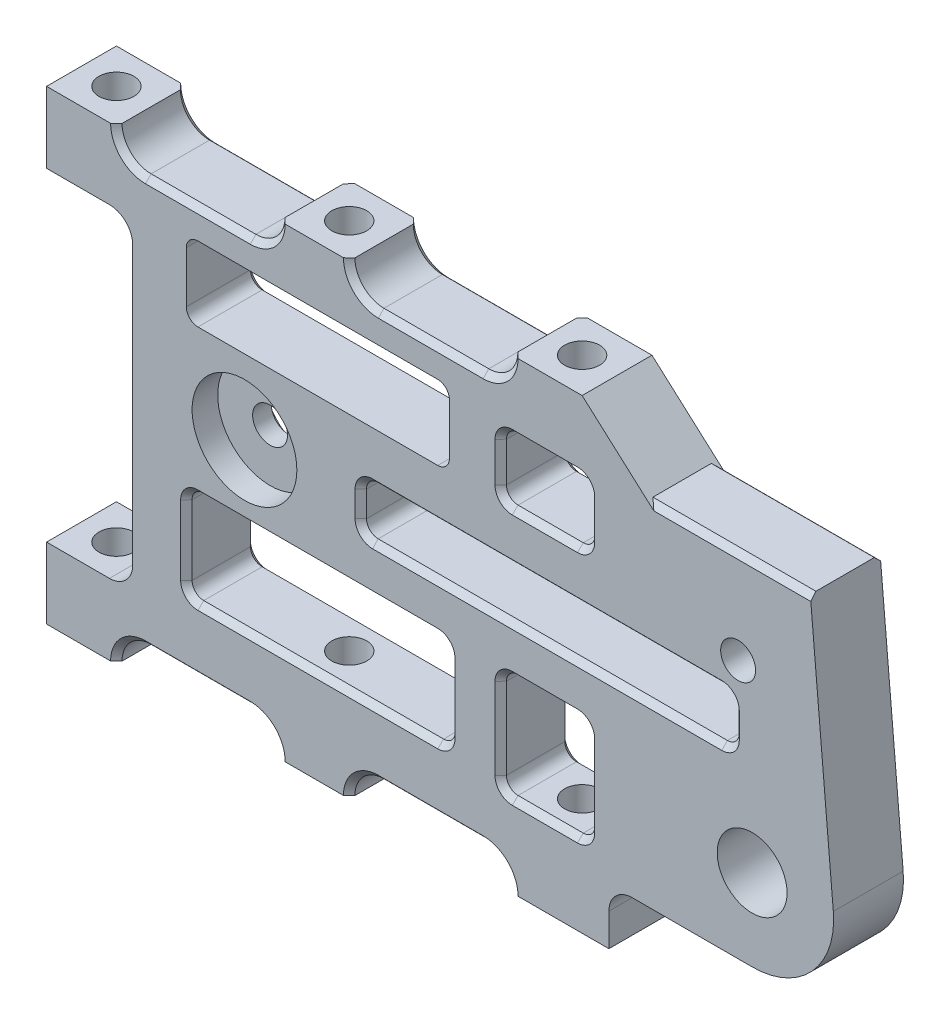
SolidWorks part; units mm, degrees
material "6061 合金"
ref_plane "前视基准面" through (0, 0, 0) normal (0, 0, 1) x (1, 0, 0)
ref_plane "上视基准面" through (0, 0, 0) normal (0, 1, 0) x (1, 0, 0)
ref_plane "右视基准面" through (0, 0, 0) normal (1, 0, 0) x (0, 0, -1)
ref_plane "基准面1" through (0, 0, 0) normal (0, 0, -1) x (-1, 0, 0)
sketch "草图1" plane through (0, 0, 0) normal (0, 0, -1) x (-1, 0, 0)
  line L0 (-32.3626, 20) -> (-35.8621, -20)
  line L1 (-35.8621, -20) -> (32.8, -20)
  line L2 (32.8, -20) -> (32.8, 20)
  line L3 (32.8, 20) -> (-32.3626, 20)
extrude "凸台-拉伸1" add sketch "草图1" against normal blind 6
sketch "草图2" plane through (0, 0, 6) normal (0, 0, 1) x (1, 0, 0)
  line L0 (35.4422, -15.2) -> (15.5, -15.2)
  line L1 (15.5, -15.2) -> (15.5, -20)
  line L2 (15.5, -20) -> (35.8621, -20)
  line L3 (35.8621, -20) -> (35.4422, -15.2)
extrude "切除-拉伸1" cut sketch "草图2" against normal through all
sketch "草图3" plane through (0, 0, 6) normal (0, 0, 1) x (1, 0, 0)
  line L0 (-6.8, -20) -> (7.2, -20)
  line L1 (4.7, -17.5) -> (-4.3, -17.5)
  arc A0 (7.2, -20) -> (4.7, -17.5) centre (4.7, -20) ccw
  arc A1 (-4.3, -17.5) -> (-6.8, -20) centre (-4.3, -20) ccw
extrude "切除-拉伸2" cut sketch "草图3" against normal through all
sketch "草图4" plane through (0, 0, 6) normal (0, 0, 1) x (1, 0, 0)
  line L0 (-26.8, -20) -> (-12.8, -20)
  line L1 (-15.3, -17.5) -> (-24.3, -17.5)
  arc A0 (-12.8, -20) -> (-15.3, -17.5) centre (-15.3, -20) ccw
  arc A1 (-24.3, -17.5) -> (-26.8, -20) centre (-24.3, -20) ccw
extrude "切除-拉伸3" cut sketch "草图4" against normal through all
sketch "草图5" plane through (0, 0, 6) normal (0, 0, 1) x (1, 0, 0)
  line L0 (-32.8, 13.9) -> (-32.8, -13.9)
  line L1 (-32.8, -13.9) -> (-25.4, -13.9)
  line L2 (-25.4, -13.9) -> (-25.4, 13.9)
  line L3 (-25.4, 13.9) -> (-32.8, 13.9)
extrude "切除-拉伸4" cut sketch "草图5" against normal through all
sketch "草图6" plane through (0, 0, 6) normal (0, 0, 1) x (1, 0, 0)
  line L0 (-12.8, 20) -> (-26.8, 20)
  line L1 (-24.3, 17.5) -> (-15.3, 17.5)
  arc A0 (-26.8, 20) -> (-24.3, 17.5) centre (-24.3, 20) ccw
  arc A1 (-15.3, 17.5) -> (-12.8, 20) centre (-15.3, 20) ccw
extrude "切除-拉伸5" cut sketch "草图6" against normal through all
sketch "草图7" plane through (0, 0, 6) normal (0, 0, 1) x (1, 0, 0)
  line L0 (7.2, 20) -> (-6.8, 20)
  line L1 (-4.3, 17.5) -> (4.7, 17.5)
  arc A0 (-6.8, 20) -> (-4.3, 17.5) centre (-4.3, 20) ccw
  arc A1 (4.7, 17.5) -> (7.2, 20) centre (4.7, 20) ccw
extrude "切除-拉伸6" cut sketch "草图7" against normal through all
sketch "草图8" plane through (0, 0, 6) normal (0, 0, 1) x (1, 0, 0)
  line L0 (13.2, 20) -> (18.8, 15)
  line L1 (18.8, 15) -> (32.8, 15)
  line L2 (32.8, 15) -> (32.3626, 20)
  line L3 (32.3626, 20) -> (13.2, 20)
extrude "切除-拉伸7" cut sketch "草图8" against normal through all
sketch "草图9" plane through (0, 0, 0) normal (0, 0, -1) x (-1, 0, 0)
  line L0 (-13.8, -13) -> (-6.2, -13)
  line L1 (-6.2, -13) -> (-6.2, -4)
  line L2 (-6.2, -4) -> (-13.8, -4)
  line L3 (-13.8, -4) -> (-13.8, -13)
extrude "切除-拉伸8" cut sketch "草图9" against normal through all
sketch "草图10" plane through (0, 0, 0) normal (0, 0, -1) x (-1, 0, 0)
  line L0 (-1.8, -12) -> (20.8, -12)
  line L1 (20.8, -12) -> (20.8, -4)
  line L2 (20.8, -4) -> (-1.8, -4)
  line L3 (-1.8, -4) -> (-1.8, -12)
extrude "切除-拉伸9" cut sketch "草图10" against normal through all
sketch "草图11" plane through (0, 0, 0) normal (0, 0, -1) x (-1, 0, 0)
  line L0 (-1.8, 15) -> (-1.8, 8.6)
  line L1 (-1.8, 8.6) -> (20.8, 8.6)
  line L2 (20.8, 8.6) -> (20.8, 15)
  line L3 (20.8, 15) -> (-1.8, 15)
extrude "切除-拉伸10" cut sketch "草图11" against normal through all
sketch "草图12" plane through (0, 0, 0) normal (0, 0, -1) x (-1, 0, 0)
  line L0 (-13.8, 8.6) -> (-6.2, 8.6)
  line L1 (-6.2, 8.6) -> (-6.2, 14)
  line L2 (-6.2, 14) -> (-13.8, 14)
  line L3 (-13.8, 14) -> (-13.8, 8.6)
extrude "切除-拉伸11" cut sketch "草图12" against normal through all
sketch "草图13" plane through (0, 0, 6) normal (0, 0, 1) x (1, 0, 0)
  line L0 (-5.8, 0.1) -> (26.2, 0.1)
  line L1 (26.2, 0.1) -> (26.2, 4.3)
  line L2 (26.2, 4.3) -> (-5.8, 4.3)
  line L3 (-5.8, 4.3) -> (-5.8, 0.1)
extrude "切除-拉伸12" cut sketch "草图13" against normal through all
hole_wizard "Ø3.0 (3) 直径孔1" positions "草图15" profile "草图14" hole size "Ø3.0" standard "ANSI Metric"
sketch "草图15" plane through (0, 0, 6) normal (0, 0, 1) x (1, 0, 0)
  point P0 (26.6, 7)
sketch "草图14" plane through (26.6, 7, 6) normal (1, 0, 0) x (0, -1, 0)
  line L0 (0, 0) -> (0, 6)
  line L1 (0, 6) -> (1.5, 6)
  line L2 (1.5, 6) -> (1.5, 0)
  line L5 (1.5, 0) -> (0, 0)
  line L11 (0, -6.35) -> (0, 107.95) construction
  dimension "通孔孔直径" = 3
  dimension "通孔孔深度" = 6
hole_wizard "Ø6.0 (6) 直径孔1" positions "草图17" profile "草图16" hole size "Ø6.0" standard "ANSI Metric"
sketch "草图17" plane through (0, 0, 6) normal (0, 0, 1) x (1, 0, 0)
  point P0 (27.803, -8.2)
sketch "草图16" plane through (27.803, -8.2, 6) normal (1, 0, 0) x (0, -1, 0)
  line L0 (0, 0) -> (0, 6)
  line L1 (0, 6) -> (3, 6)
  line L2 (3, 6) -> (3, 0)
  line L5 (3, 0) -> (0, 0)
  line L11 (0, -6.35) -> (0, 107.95) construction
  dimension "通孔孔直径" = 6
  dimension "通孔孔深度" = 6
hole_wizard "Ø3.0 (3) 直径孔2" positions "草图19" profile "草图18" hole size "Ø3.0" standard "ANSI Metric"
sketch "草图19" plane through (0, -13, 0) normal (0, 1, 0) x (1, 0, 0)
  point P0 (10.2, -3)
cosmetic thread "装饰螺纹线4" parameters "D2"=3.5
sketch "草图18" plane through (10.2, -13, 3) normal (1, 0, 0) x (0, 0, 1)
  line L0 (0, 0) -> (0, 7)
  line L1 (0, 7) -> (1.5, 7)
  line L2 (1.5, 7) -> (1.5, 0)
  line L5 (1.5, 0) -> (0, 0)
  line L11 (0, -6.35) -> (0, 107.95) construction
  dimension "通孔孔直径" = 3
  dimension "通孔孔深度" = 7
hole_wizard "Ø3.0 (3) 直径孔3" positions "草图21" profile "草图20" hole size "Ø3.0" standard "ANSI Metric"
sketch "草图21" plane through (0, -12, 0) normal (0, 1, 0) x (1, 0, 0)
  point P0 (-9.8, -3)
sketch "草图20" plane through (-9.8, -12, 3) normal (1, 0, 0) x (0, 0, 1)
  line L0 (0, 0) -> (0, 8)
  line L1 (0, 8) -> (1.5, 8)
  line L2 (1.5, 8) -> (1.5, 0)
  line L5 (1.5, 0) -> (0, 0)
  line L11 (0, -6.35) -> (0, 107.95) construction
  dimension "通孔孔直径" = 3
  dimension "通孔孔深度" = 8
cosmetic thread "装饰螺纹线5" parameters "D2"=3.5
hole_wizard "Ø3.0 (3) 直径孔4" positions "草图23" profile "草图22" hole size "Ø3.0" standard "ANSI Metric"
sketch "草图23" plane through (0, 15, 0) normal (0, -1, 0) x (-1, 0, 0)
  point P0 (9.8, -3)
sketch "草图22" plane through (-9.8, 15, 3) normal (1, 0, 0) x (0, 0, -1)
  line L0 (0, 0) -> (0, 5)
  line L1 (0, 5) -> (1.5, 5)
  line L2 (1.5, 5) -> (1.5, 0)
  line L5 (1.5, 0) -> (0, 0)
  line L11 (0, -6.35) -> (0, 107.95) construction
  dimension "通孔孔直径" = 3
  dimension "通孔孔深度" = 5
cosmetic thread "装饰螺纹线2" parameters "D2"=3.5
hole_wizard "Ø3.0 (3) 直径孔5" positions "草图25" profile "草图24" hole size "Ø3.0" standard "ANSI Metric"
sketch "草图25" plane through (0, 14, 0) normal (0, -1, 0) x (-1, 0, 0)
  point P0 (-10.2, -3)
sketch "草图24" plane through (10.2, 14, 3) normal (1, 0, 0) x (0, 0, -1)
  line L0 (0, 0) -> (0, 6)
  line L1 (0, 6) -> (1.5, 6)
  line L2 (1.5, 6) -> (1.5, 0)
  line L5 (1.5, 0) -> (0, 0)
  line L11 (0, -6.35) -> (0, 107.95) construction
  dimension "通孔孔直径" = 3
  dimension "通孔孔深度" = 6
cosmetic thread "装饰螺纹线3" parameters "D2"=3.5
hole_wizard "Ø3.0 (3) 直径孔6" positions "草图27" profile "草图26" hole size "Ø3.0" standard "ANSI Metric"
sketch "草图27" plane through (0, -20, 0) normal (0, -1, 0) x (-1, 0, 0)
  point P0 (29.8, -3)
sketch "草图26" plane through (-29.8, -20, 3) normal (1, 0, 0) x (0, 0, -1)
  line L0 (0, 0) -> (0, 6.1)
  line L1 (0, 6.1) -> (1.5, 6.1)
  line L2 (1.5, 6.1) -> (1.5, 0)
  line L5 (1.5, 0) -> (0, 0)
  line L11 (0, -6.35) -> (0, 107.95) construction
  dimension "通孔孔直径" = 3
  dimension "通孔孔深度" = 6.1
cosmetic thread "装饰螺纹线6" parameters "D2"=3.5
hole_wizard "Ø3.0 (3) 直径孔7" positions "草图29" profile "草图28" hole size "Ø3.0" standard "ANSI Metric" end condition through all
sketch "草图29" plane through (0, 13.9, 0) normal (0, -1, 0) x (-1, 0, 0)
  point P0 (29.8, -3)
sketch "草图28" plane through (-29.8, 13.9, 3) normal (1, 0, 0) x (0, 0, -1)
  line L0 (0, 0) -> (0, 6.1)
  line L1 (0, 6.1) -> (1.5, 6.1)
  line L2 (1.5, 6.1) -> (1.5, 0)
  line L5 (1.5, 0) -> (0, 0)
  line L11 (0, -6.35) -> (0, 107.95) construction
  dimension "通孔孔直径" = 3
  dimension "通孔孔深度" = 6.1
cosmetic thread "装饰螺纹线1" parameters "D2"=3.5
hole_wizard "M2.5 六角头机械螺钉的柱形沉头孔1" positions "草图31" profile "草图30" counterbore size "M2.5" standard "ANSI Metric"
sketch "草图31" plane through (0, 0, 0) normal (0, 0, -1) x (-1, 0, 0)
  point P0 (15.8, 2.2)
sketch "草图30" plane through (-15.8, 2.2, 0) normal (1, 0, 0) x (0, 1, 0)
  line L0 (0, 0) -> (0, 6)
  line L1 (0, 6) -> (1.5, 6)
  line L3 (1.5, 6) -> (1.5, 2.2)
  line L4 (1.5, 2.2) -> (4.5, 2.2)
  line L5 (4.5, 2.2) -> (4.5, 0)
  line L7 (4.5, 0) -> (0, 0)
  line L11 (0, -6.35) -> (0, 107.95) construction
  dimension "通孔孔直径" = 3
  dimension "通孔孔深度" = 6
  dimension "柱形沉头孔直径" = 9
  dimension "柱形沉头孔深度" = 2.2
fillet "圆角1" radius 1 20 edges at (-20.8, 15, 3) (13.8, 14, 3) (13.8, 8.6, 3) (-20.8, -12, 3) (1.8, 15, 3) (-5.8, 0.1, 3) (1.8, -12, 3) (26.2, 4.3, 3) (6.2, 8.6, 3) (13.8, -13, 3) (6.2, 14, 3) (6.2, -13, 3) (1.8, 8.6, 3) (13.8, -4, 3) (-20.8, 8.6, 3) (6.2, -4, 3) (-5.8, 4.3, 3) (1.8, -4, 3) (26.2, 0.1, 3) (-20.8, -4, 3)
fillet "圆角2" radius 2 3 edges at (-25.4, -13.9, 3) (-25.4, 13.9, 3) (15.5, -15.2, 3)
fillet "圆角3" radius 7 1 edges at (35.4422, -15.2, 3)
chamfer "倒角1" distance 0.5 angle 44 99 edges at (25.8, 15, 0) (25.8, 15, 6) (-26.0678, 18.2322, 6) (-13.5322, 18.2322, 6) (-19.8, 17.5, 6) (-6.0678, 18.2322, 6) (6.4678, 18.2322, 6) (0.2, 17.5, 6) (6.2, 11.3, 6) (6.4929, 13.7071, 6) (6.4929, 8.8929, 6) (10, 14, 6) (10, 8.6, 6) (13.5071, 13.7071, 6) (13.5071, 8.8929, 6) (13.8, 11.3, 6) (-5.8, 2.2, 6) (-5.5071, 0.3929, 6) (-5.5071, 4.0071, 6) (10.2, 0.1, 6) (10.2, 4.3, 6) (25.9071, 0.3929, 6) (25.9071, 4.0071, 6) (26.2, 2.2, 6) (-20.8, -8, 6) (-20.5071, -4.2929, 6) (-20.5071, -11.7071, 6) (-9.5, -4, 6) (-9.5, -12, 6) (1.5071, -4.2929, 6) (1.5071, -11.7071, 6) (1.8, -8, 6) (6.2, -8.5, 6) (6.4929, -4.2929, 6) (6.4929, -12.7071, 6) (10, -4, 6) (10, -13, 6) (13.5071, -4.2929, 6) (13.5071, -12.7071, 6) (13.8, -8.5, 6) (-20.8, -8, 0) (-20.5071, -4.2929, 0) (-20.5071, -11.7071, 0) (-9.5, -4, 0) (-9.5, -12, 0) (1.5071, -4.2929, 0) (1.5071, -11.7071, 0) (1.8, -8, 0) (6.2, -8.5, 0) (6.4929, -4.2929, 0) (6.4929, -12.7071, 0) (10, -4, 0) (10, -13, 0) (13.5071, -4.2929, 0) (13.5071, -12.7071, 0) (13.8, -8.5, 0) (-5.8, 2.2, 0) (-5.5071, 0.3929, 0) (-5.5071, 4.0071, 0) (10.2, 0.1, 0) (10.2, 4.3, 0) (25.9071, 0.3929, 0) (25.9071, 4.0071, 0) (26.2, 2.2, 0) (6.2, 11.3, 0) (6.4929, 13.7071, 0) (6.4929, 8.8929, 0) (10, 14, 0) (10, 8.6, 0) (13.5071, 13.7071, 0) (13.5071, 8.8929, 0) (13.8, 11.3, 0) (-20.8, 11.8, 0) (-20.5071, 14.7071, 0) (-20.5071, 8.8929, 0) (-9.5, 15, 0) (-9.5, 8.6, 0) (1.5071, 14.7071, 0) (1.5071, 8.8929, 0) (1.8, 11.8, 0) (-26.0678, 18.2322, 0) (-19.8, 17.5, 0) (-13.5322, 18.2322, 0) (-6.0678, 18.2322, 0) (6.4678, 18.2322, 0) (0.2, 17.5, 0) (30.803, -8.2, 0) (6.4678, -18.2322, 6) (-6.0678, -18.2322, 6) (0.2, -17.5, 6) (-13.5322, -18.2322, 6) (-26.0678, -18.2322, 6) (-19.8, -17.5, 6) (-13.5322, -18.2322, 0) (-26.0678, -18.2322, 0) (-19.8, -17.5, 0) (6.4678, -18.2322, 0) (-6.0678, -18.2322, 0) (0.2, -17.5, 0)
sketch "草图32" plane through (0, 0, 6) normal (0, 0, 1) x (1, 0, 0)
  circle A0 centre (-15.8, 2.2) radius 4.5
  dimension "D1" = 9
extrude "切除-拉伸14" cut sketch "草图32" against normal blind 2.2
